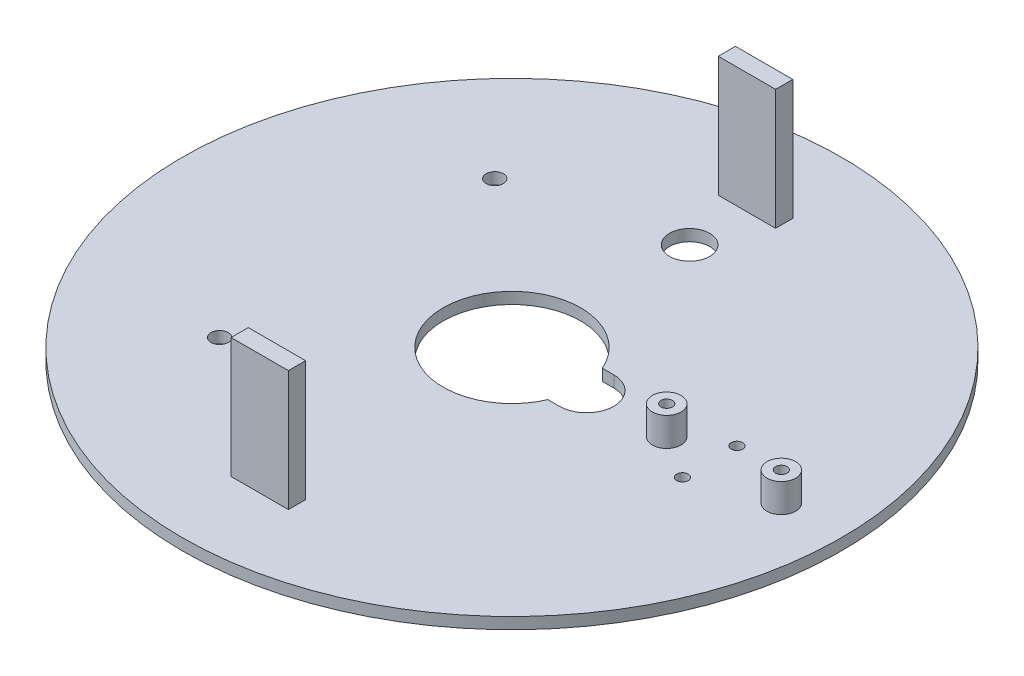
SolidWorks part; units mm, degrees
ref_plane "Plan de face" through (0, 0, 0) normal (0, 0, 1) x (1, 0, 0)
ref_plane "Plan de dessus" through (0, 0, 0) normal (0, 1, 0) x (1, 0, 0)
ref_plane "Plan de droite" through (0, 0, 0) normal (1, 0, 0) x (0, 0, -1)
sketch "Esquisse1" plane through (0, 0, 0) normal (0, 1, 0) x (1, 0, 0)
  circle A0 centre (0, 0) radius 57.5
extrude "Boss.-Extru.1" add sketch "Esquisse1" along normal blind 2
sketch "Esquisse2" plane through (0, 2, 0) normal (0, 1, 0) x (1, 0, 0)
  circle A0 centre (0, 0) radius 12
extrude "Enlèv. mat.-Extru.1" cut sketch "Esquisse2" against normal blind 3
sketch "Esquisse5" plane through (0, 2, 0) normal (0, 1, 0) x (1, 0, 0)
  line L0 (0, 12) -> (0, 44) construction
  line L1 (0, -12) -> (0, -44) construction
  line L2 (0, 44) -> (-5, 44) construction
  line L3 (0, 44) -> (5, 44) construction
  line L4 (0, -44) -> (-5, -44) construction
  line L6 (-5, -44) -> (5, -44)
  line L7 (-5, -44) -> (-5, -41)
  line L8 (-5, -41) -> (5, -41)
  line L9 (5, -44) -> (5, -41)
  line L10 (-5, 44) -> (5, 44)
  line L11 (-5, 44) -> (-5, 41)
  line L12 (-5, 41) -> (5, 41)
  line L13 (5, 44) -> (5, 41)
  circle A0 centre (0, 0) radius 12 construction
  dimension "D1" = 3
  dimension "D2" = 10
  dimension "D3" = 3
  dimension "D4" = 10
extrude "Boss.-Extru.3" add sketch "Esquisse5" along normal blind 21
sketch "Esquisse8" plane through (0, 2, 0) normal (0, 1, 0) x (1, 0, 0)
  line L2 (27, 0) -> (47, 0) construction
  circle A0 centre (27, 0) radius 2.5
  circle A1 centre (47, 0) radius 2.5
  circle A2 centre (27, 0) radius 1
  circle A3 centre (47, 0) radius 1
  point P2 (0, 0)
extrude "Boss.-Extru.4" add sketch "Esquisse8" along normal blind 5
sketch "Esquisse11" plane through (0, 2, 0) normal (0, 1, 0) x (1, 0, 0)
  circle A1 centre (0, 31) radius 3.5
extrude "Enlèv. mat.-Extru.7" cut sketch "Esquisse11" against normal through all
sketch "Esquisse12" plane through (0, 2, 0) normal (0, 1, 0) x (1, 0, 0)
  line L0 (-27, 0) -> (-27, 24) construction
  line L1 (-12, 0) -> (-27, 0) construction
  line L2 (-27, 0) -> (-27, -24) construction
  circle A0 centre (0, 0) radius 12 construction
  circle A1 centre (-27, 24) radius 1.5
  circle A2 centre (-27, -24) radius 1.5
extrude "Enlèv. mat.-Extru.8" cut sketch "Esquisse12" against normal through all and the other way through all
sketch "Esquisse14" plane through (0, 2, 0) normal (0, 1, 0) x (1, 0, 0)
  line L0 (29.5, 0) -> (34.5, 0) construction
  line L1 (34.5, 0) -> (34.5, 4.75) construction
  line L2 (34.5, 0) -> (34.5, -4.75) construction
  line L3 (12, 0) -> (13.0199, 0) construction
  line L4 (11.0199, -4.75) -> (13.0199, -4.75)
  line L5 (13.0199, 4.75) -> (11.0199, 4.75)
  line L6 (11.0199, 4.75) -> (11.0199, -4.75)
  circle A0 centre (27, 0) radius 2.5 construction
  circle A1 centre (34.5, -4.75) radius 1
  circle A2 centre (34.5, 4.75) radius 1
  circle A3 centre (0, 0) radius 12 construction
  arc A4 (13.0199, 4.75) -> (13.0199, -4.75) centre (13.0199, 0) cw
extrude "Enlèv. mat.-Extru.10" cut sketch "Esquisse14" against normal through all
